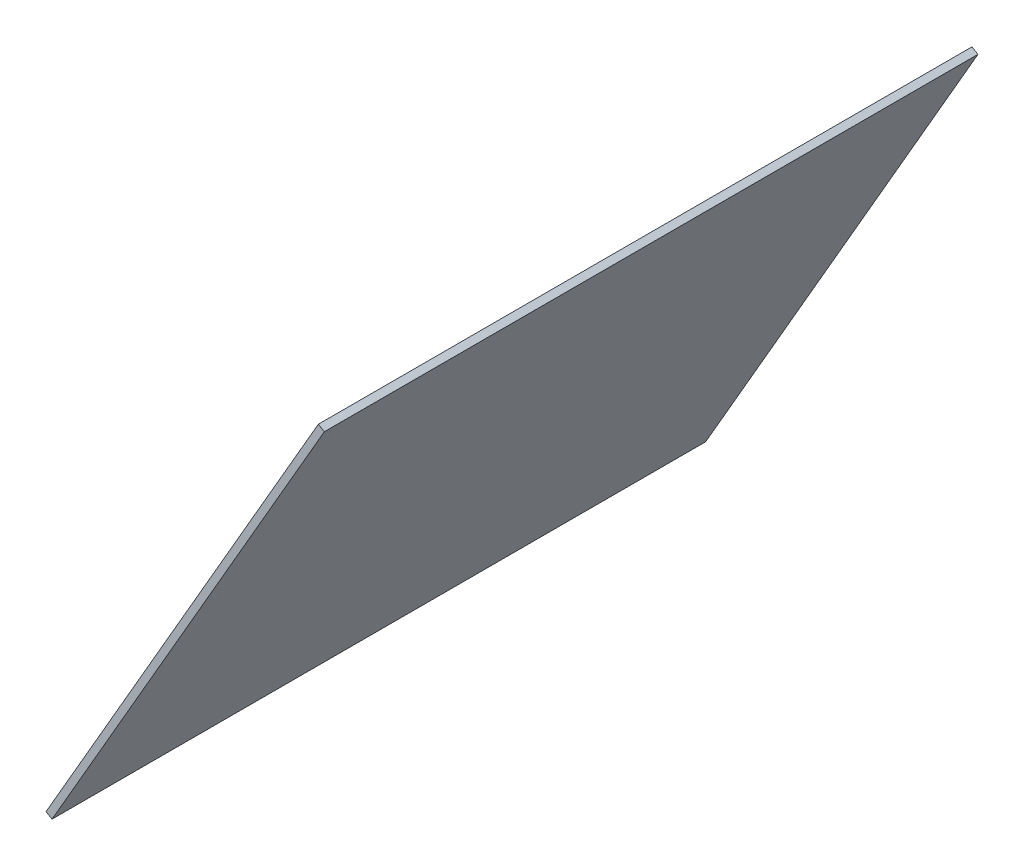
SolidWorks part; units mm, degrees
ref_plane "Front Plane" through (0, 0, 0) normal (0, 0, 1) x (1, 0, 0)
ref_plane "Top Plane" through (0, 0, 0) normal (0, 1, 0) x (1, 0, 0)
ref_plane "Right Plane" through (0, 0, 0) normal (1, 0, 0) x (0, 0, -1)
sketch "Sketch2" plane through (0, 0, 279) normal (0, 0, 1) x (1, 0, 0)
  line L4 (146.3249, 0) -> (263.8249, 203.516)
  line L5 (146.3249, 0) -> (148.9229, -1.5)
  line L6 (263.8249, 203.516) -> (266.4229, 202.016)
  line L7 (148.9229, -1.5) -> (266.4229, 202.016)
  line L8 (146.3249, 0) -> (267.5, 209.8815) construction
  dimension "D1" = 3
  dimension "D2" = 235
extrude "Boss-Extrude1" add sketch "Sketch2" against normal up to surface (282 mm away) contours L6 L7 L5 L4
